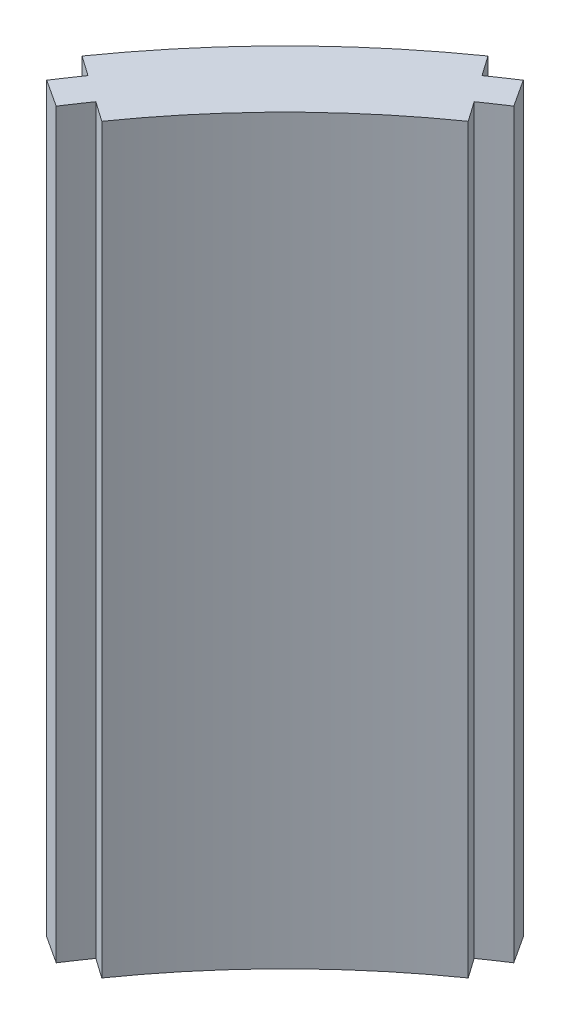
SolidWorks part; units mm, degrees
material "PLA"
ref_plane "Front Plane" through (0, 0, 0) normal (0, 0, 1) x (1, 0, 0)
ref_plane "Top Plane" through (0, 0, 0) normal (0, 1, 0) x (1, 0, 0)
ref_plane "Right Plane" through (0, 0, 0) normal (1, 0, 0) x (0, 0, -1)
sketch "Sketch1" plane through (0, 0, 0) normal (0, 1, 0) x (1, 0, 0)
  line L0 (0, -1.9192) -> (0, 0) construction
  line L1 (0, 0) -> (-18.4967, 18.4967) construction
  line L2 (-20.7002, 29.4534) -> (0, 0) construction
  line L3 (0, 0) -> (-29.4534, 20.7002) construction
  line L4 (-29.4534, 20.7002) -> (-28.5943, 20.0964)
  line L5 (-20.7002, 29.4534) -> (-20.0964, 28.5943)
  line L6 (-18.2706, 28.1387) -> (-19.0351, 29.3115)
  line L7 (-28.1387, 18.2706) -> (-29.3115, 19.0351)
  line L8 (-19.2914, 27.4489) -> (-18.6877, 26.5899)
  line L9 (-27.4489, 19.2914) -> (-26.5899, 18.6877)
  arc A1 (-18.6877, 26.5899) -> (-26.5899, 18.6877) centre (0, 0) ccw
  arc A2 (-20.7002, 29.4534) -> (-29.4534, 20.7002) centre (0, 0) ccw
  arc A3 (-27.4489, 19.2914) -> (-28.1387, 18.2706) centre (0, 0) ccw
  arc A4 (-28.5943, 20.0964) -> (-29.3115, 19.0351) centre (0, 0) ccw
  arc A5 (-18.2706, 28.1387) -> (-19.2914, 27.4489) centre (0, 0) ccw
  arc A6 (-19.0351, 29.3115) -> (-20.0964, 28.5943) centre (0, 0) ccw
  dimension "D1" = 45
  dimension "D2" = 9.9
  dimension "D4" = 32.5
  dimension "D5" = 69.9
  dimension "D6" = 67.1
  dimension "D3" = 9.9
  dimension "D7" = 11.9
  dimension "D8" = 11.9
extrude "Boss-Extrude1" add sketch "Sketch1" along normal blind 32
